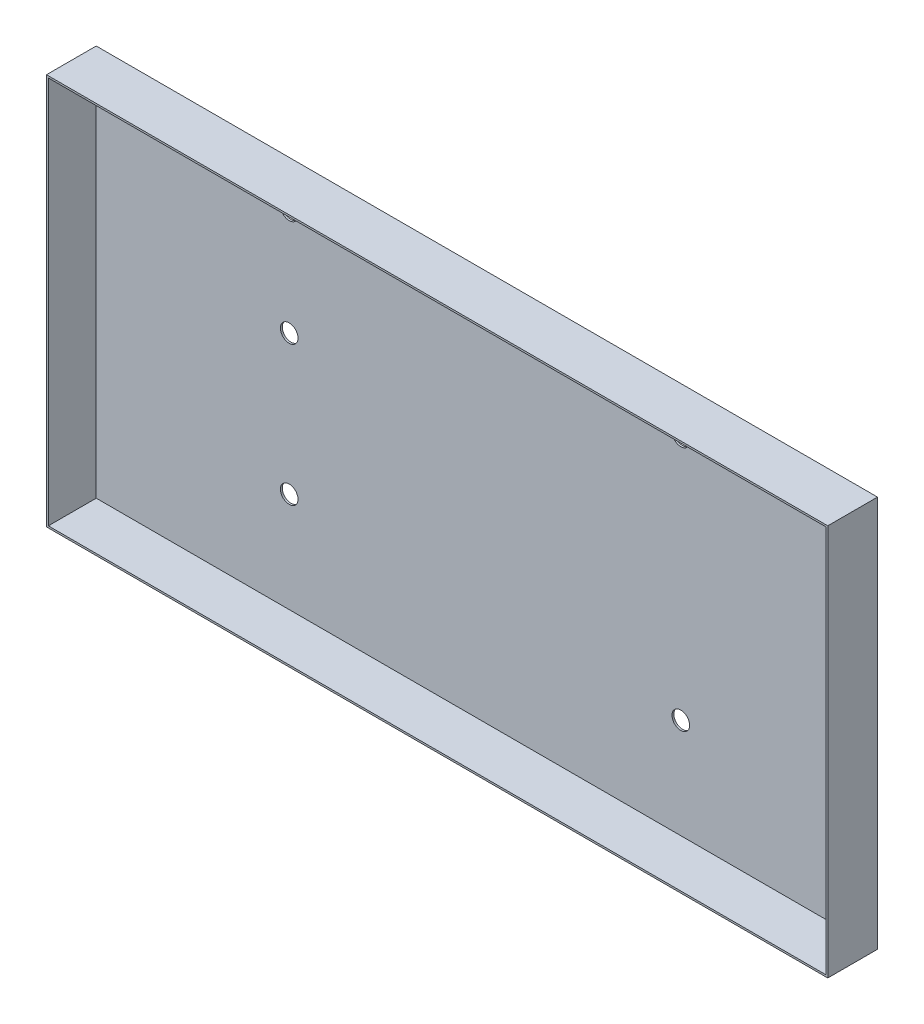
SolidWorks part; units mm, degrees
ref_plane "Alzado" through (0, 0, 0) normal (0, 0, 1) x (1, 0, 0)
ref_plane "Planta" through (0, 0, 0) normal (0, 1, 0) x (1, 0, 0)
ref_plane "Vista lateral" through (0, 0, 0) normal (1, 0, 0) x (0, 0, -1)
sketch "Croquis1" plane through (0, 0, 0) normal (0, 0, 1) x (1, 0, 0)
  line L0 (-798, 400) -> (-798, 0)
  line L1 (-798, 0) -> (0, 0)
  line L2 (0, 0) -> (0, 400)
  line L3 (0, 400) -> (-798, 400)
  circle A0 centre (-599, 355) radius 9
  circle A1 centre (-599, 246.5) radius 9
  circle A2 centre (-599, 104) radius 9
  circle A3 centre (-199, 104) radius 9
  circle A4 centre (-199, 355) radius 9
  dimension "D3" = 18
  dimension "D5" = 18
  dimension "D6" = 18
  dimension "D7" = 18
  dimension "D8" = 18
  dimension "D10" = 108.5
  dimension "D11" = 142.5
  dimension "D12" = 251
  dimension "D15" = 199
  dimension "D16" = 199
  dimension "D4" = 45
  dimension "D9" = 45
  dimension "D1" = 400
  dimension "D2" = 798
  dimension "D13" = 199
  dimension "D14" = 199
  dimension "D17" = 199
extrude "Saliente-Extruir1" add sketch "Croquis1" along normal blind 50.8
shell "Vaciado1" thickness 1.9
sketch "Croquis2" plane through (0, 0, 50.8) normal (0, 0, 1) x (1, 0, 0)
  line L0 (-1.9, 1.9) -> (-1.9, 398.1)
  line L1 (-1.9, 398.1) -> (-796.1, 398.1)
  line L2 (-796.1, 398.1) -> (-796.1, 1.9)
  line L3 (-796.1, 1.9) -> (-1.9, 1.9)
extrude "Cortar-Extruir1" cut sketch "Croquis2" against normal blind 48.9
